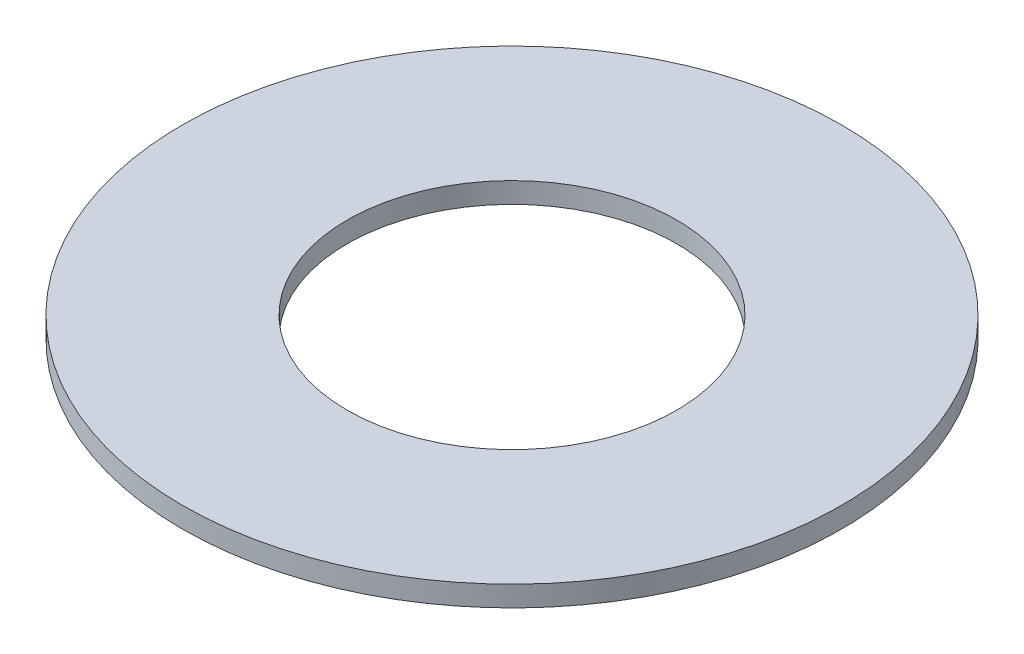
SolidWorks part; units mm, degrees
ref_plane "Front" through (0, 0, 0) normal (0, 0, 1) x (1, 0, 0)
ref_plane "Top" through (0, 0, 0) normal (0, 1, 0) x (1, 0, 0)
ref_plane "Right" through (0, 0, 0) normal (1, 0, 0) x (0, 0, -1)
sketch "Sketch1" plane through (0, 0, 0) normal (0, 1, 0) x (1, 0, 0)
  circle A0 centre (0, 0) radius 12.7
  circle A1 centre (0, 0) radius 6.35
  dimension "D1" = 25.4
  dimension "D2" = 12.7
extrude "Boss-Extrude1" add sketch "Sketch1" along normal blind 0.7937
